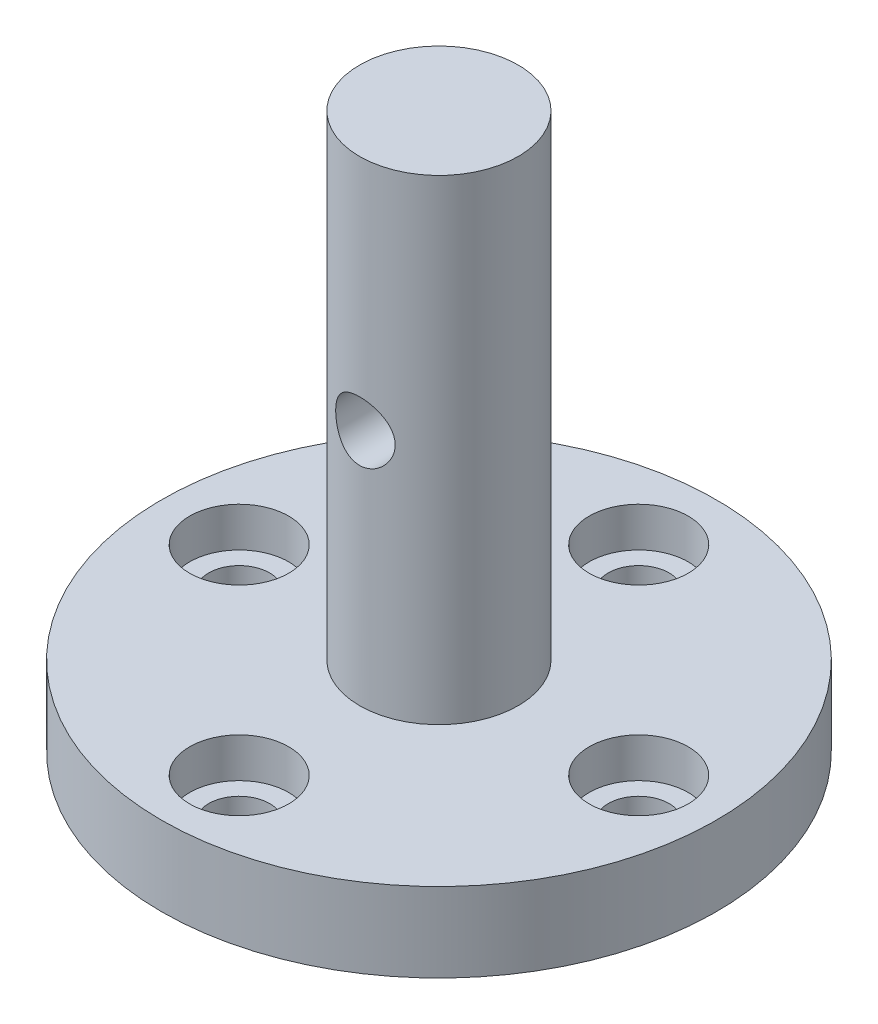
SolidWorks part; units mm, degrees
material "6061-T6 (SS)"
ref_plane "Front Plane" through (0, 0, 0) normal (0, 0, 1) x (1, 0, 0)
ref_plane "Top Plane" through (0, 0, 0) normal (0, 1, 0) x (1, 0, 0)
ref_plane "Right Plane" through (0, 0, 0) normal (1, 0, 0) x (0, 0, -1)
sketch "Sketch1" plane through (0, 0, 0) normal (0, 1, 0) x (1, 0, 0)
  circle A0 centre (0, 0) radius 11.1125
  circle A1 centre (0, 0) radius 3.175 construction
  circle A2 centre (0, 0) radius 8 construction
  dimension "D1" = 6.35
  dimension "D2" = 16
  dimension "D3" = 22.225
extrude "Boss-Extrude1" add sketch "Sketch1" along normal blind 3.175
sketch "Sketch2" plane through (0, 3.175, 0) normal (0, 1, 0) x (1, 0, 0)
  circle A0 centre (0, 0) radius 3.175
  dimension "D1" = 6.35
extrude "Boss-Extrude2" add sketch "Sketch2" along normal blind 19.05
hole_wizard "#2 Clearance Hole1" positions "Sketch3" profile "Sketch4" hole size "#2" standard "ANSI Inch" end condition through all
sketch "Sketch3" plane through (0, 3.175, 0) normal (0, 1, 0) x (1, 0, 0)
  circle A0 centre (0, 0) radius 8
  point P0 (0, -8)
  point P2 (0, 8)
  point P4 (-8, 0)
  point P6 (8, 0)
  dimension "D1" = 16
sketch "Sketch4" plane through (0, 3.175, 8) normal (1, 0, 0) x (0, 0, 1)
  line L0 (0, 0) -> (0, 3.175)
  line L1 (0, 3.175) -> (1.2192, 3.175)
  line L2 (1.2192, 3.175) -> (1.2192, 0)
  line L5 (1.2192, 0) -> (0, 0)
  line L11 (0, -6.35) -> (0, 107.95) construction
  dimension "Thru Hole Dia." = 2.4384
  dimension "Thru Hole Depth" = 3.175
sketch "Sketch5" plane through (0, 3.175, 0) normal (0, 1, 0) x (1, 0, 0)
  circle A0 centre (0, -8) radius 1.9844
  circle A1 centre (8, 0) radius 1.9844
  circle A2 centre (0, 8) radius 1.9844
  circle A3 centre (-8, 0) radius 1.9844
  dimension "D1" = 3.9688
extrude "Cut-Extrude1" cut sketch "Sketch5" against normal blind 1.5875
ref_plane "Plane1" through (0, 0, 3.175) normal (0, 0, 1) x (1, 0, 0)
hole_wizard "3/32 (0.09375) Diameter Hole1" positions "Sketch7" profile "Sketch8" hole size "3/32" standard "ANSI Inch" end condition through all
sketch "Sketch7" plane through (0, 0, 3.175) normal (0, 0, 1) x (1, 0, 0)
  line L0 (3.175, 3.175) -> (-3.175, 3.175) construction
  line L1 (3.175, 3.175) -> (-3.175, 3.175) construction
  line L2 (3.175, 22.225) -> (-3.175, 22.225) construction
  line L3 (3.175, 22.225) -> (-3.175, 22.225) construction
  line L4 (0, 22.225) -> (0, 3.175) construction
  point P0 (0, 12.7)
  point P11 (0, 0)
  point P12 (0, 12.7)
sketch "Sketch8" plane through (0, 12.7, 3.175) normal (1, 0, 0) x (0, -1, 0)
  line L0 (0, 0) -> (0, 14.2875)
  line L1 (0, 14.2875) -> (1.1906, 14.2875)
  line L2 (1.1906, 14.2875) -> (1.1906, 0)
  line L5 (1.1906, 0) -> (0, 0)
  line L11 (0, -6.35) -> (0, 107.95) construction
  dimension "Thru Hole Dia." = 2.3812
  dimension "Thru Hole Depth" = 14.2875
